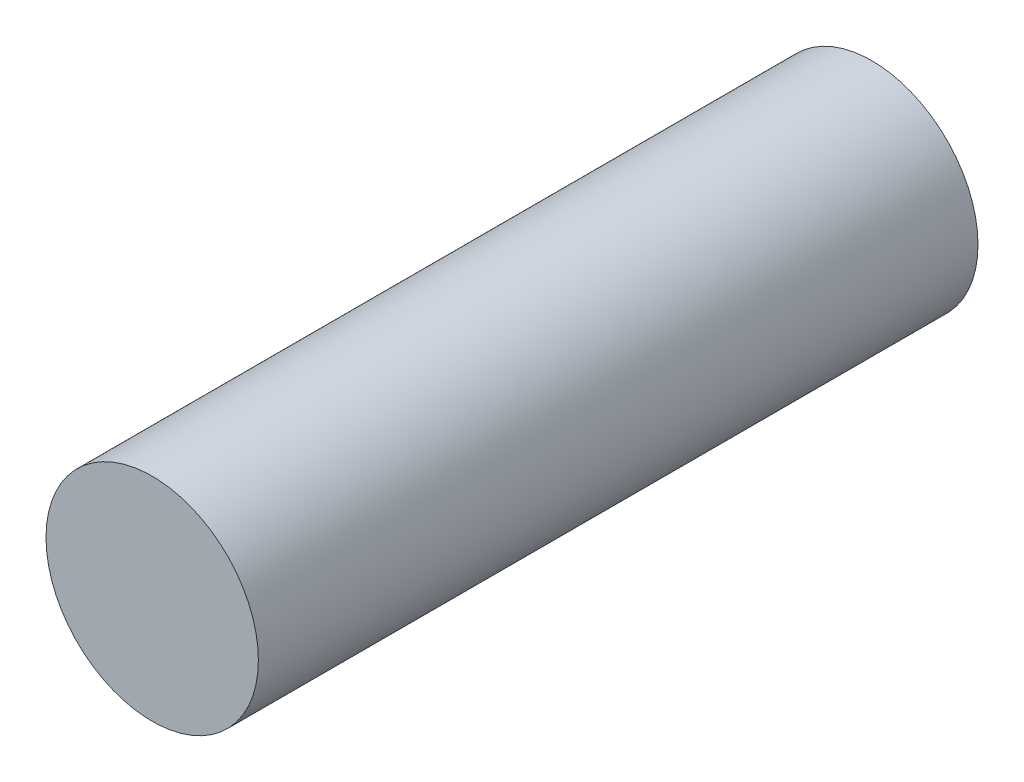
SolidWorks part; units mm, degrees
ref_plane "Front Plane" through (0, 0, 0) normal (0, 0, 1) x (1, 0, 0)
ref_plane "Top Plane" through (0, 0, 0) normal (0, 1, 0) x (1, 0, 0)
ref_plane "Right Plane" through (0, 0, 0) normal (1, 0, 0) x (0, 0, -1)
sketch "CurveSketch" plane through (0, 0, 0) normal (0, 0, 1) x (1, 0, 0)
  circle A0 centre (-3.719, 5.173) radius 1.731
  dimension "D1" = 1.731
extrude "CurveBoss" add sketch "CurveSketch" along normal blind 11.731
